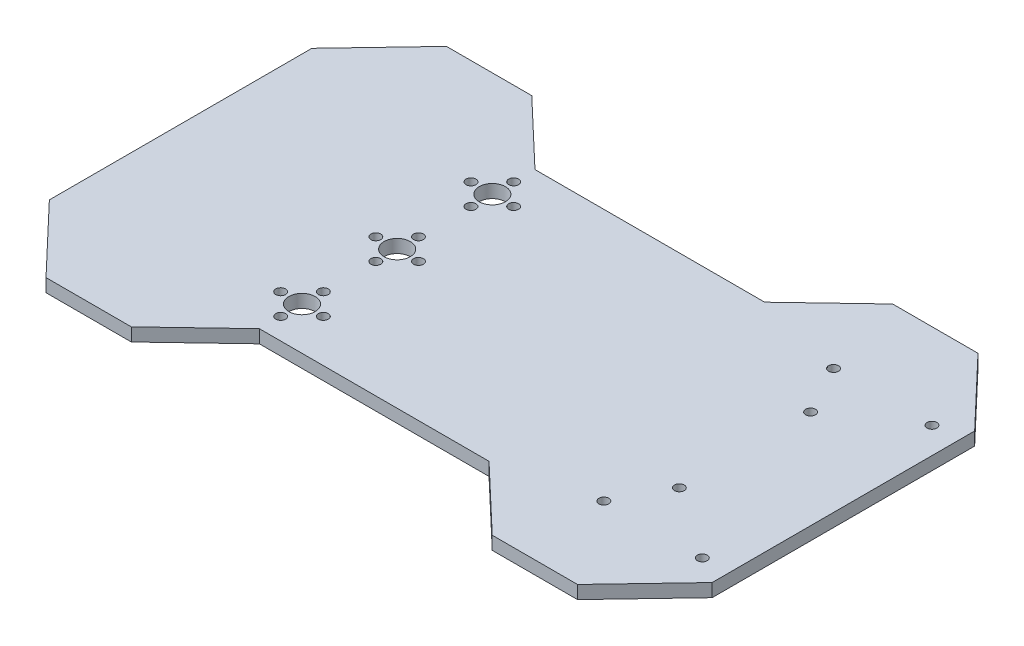
SolidWorks part; units mm, degrees
ref_plane "Front Plane" through (0, 0, 0) normal (0, 0, 1) x (1, 0, 0)
ref_plane "Top Plane" through (0, 0, 0) normal (0, 1, 0) x (1, 0, 0)
ref_plane "Right Plane" through (0, 0, 0) normal (1, 0, 0) x (0, 0, -1)
sketch "Sketch1" plane through (0, 0, 0) normal (0, 1, 0) x (1, 0, 0)
  line L0 (-101, 0) -> (101, 0) construction
  line L13 (-55, 61.025) -> (-35, 42)
  line L20 (-81, 61.025) -> (-55, 61.025)
  line L21 (-101, 40) -> (-81, 61.025)
  line L22 (-101, 40) -> (-101, -40)
  line L23 (-35, 42) -> (35, 42)
  line L24 (0, 42) -> (0, -42) construction
  line L25 (81, 61.025) -> (55, 61.025)
  line L26 (55, 61.025) -> (35, 42)
  line L27 (101, 40) -> (101, -40)
  line L28 (101, 40) -> (81, 61.025)
  line L37 (55, -61.025) -> (35, -42)
  line L38 (81, -61.025) -> (55, -61.025)
  line L39 (101, -40) -> (81, -61.025)
  line L40 (-81, -61.025) -> (-55, -61.025)
  line L41 (-55, -61.025) -> (-35, -42)
  line L42 (-101, -40) -> (-81, -61.025)
  line L46 (-35, -42) -> (35, -42)
  point P0 (0, 0)
  point P16 (0, 0)
  dimension "D1" = 20
  dimension "D2" = 84
  dimension "D3" = 40
  dimension "D4" = 35
  dimension "D5" = 26
  dimension "D6" = 202
extrude "Boss-Extrude1" add sketch "Sketch1" along normal blind 4
sketch "Sketch2" plane through (0, 4, 0) normal (0, 1, 0) x (1, 0, 0)
  line L0 (-101, 0) -> (101, 0) construction
  line L1 (-101, 40) -> (-101, -40) construction
  line L2 (101, -40) -> (101, 40) construction
sketch "Sketch3" plane through (0, 4, 0) normal (0, 1, 0) x (1, 0, 0)
  line L0 (0, 42) -> (0, -42) construction
  line L1 (35, 42) -> (-35, 42) construction
  line L2 (-35, -42) -> (35, -42) construction
  line L3 (-101, 0) -> (101, 0) construction
  circle A0 centre (-35, -29) radius 4
  circle A1 centre (-28.5, -29) radius 1.5
  circle A2 centre (-41.5, -29) radius 1.5
  circle A3 centre (-35, -22.5) radius 1.5
  circle A4 centre (-35, -35.5) radius 1.5
  circle A5 centre (-35, 35.5) radius 1.5
  circle A6 centre (-35, 22.5) radius 1.5
  circle A7 centre (-41.5, 29) radius 1.5
  circle A8 centre (-28.5, 29) radius 1.5
  circle A9 centre (-35, 29) radius 4
  circle A10 centre (-35, 0) radius 4
  circle A11 centre (-35, 6.5) radius 1.5
  circle A12 centre (-28.5, 0) radius 1.5
  circle A13 centre (-41.5, 0) radius 1.5
  circle A14 centre (-35, -6.5) radius 1.5
  point P40 (0, 0)
  point P41 (0, 0)
  dimension "D1" = 3
  dimension "D2" = 3
  dimension "D3" = 3
  dimension "D4" = 3
  dimension "D5" = 8
  dimension "D6" = 6.5
  dimension "D7" = 6.5
  dimension "D8" = 6.5
  dimension "D9" = 6.5
  dimension "D10" = 35
  dimension "D11" = 3
  dimension "D12" = 3
  dimension "D13" = 3
  dimension "D14" = 3
  dimension "D15" = 6.5
  dimension "D16" = 6.5
  dimension "D17" = 8
  dimension "D18" = 6.5
  dimension "D19" = 6.5
extrude "Cut-Extrude1" cut sketch "Sketch3" against normal through all
sketch "Sketch5" plane through (0, 4, 0) normal (0, 1, 0) x (1, 0, 0)
  line L0 (101, -40) -> (101, 40) construction
  line L1 (101, 0) -> (0, 0) construction
  circle A0 centre (93, 35) radius 1.5
  circle A1 centre (63, 35) radius 1.5
  circle A2 centre (63, -35) radius 1.5
  circle A3 centre (93, -35) radius 1.5
  dimension "D1" = 3
  dimension "D2" = 3
  dimension "D3" = 8
  dimension "D4" = 70
  dimension "D5" = 30
extrude "Cut-Extrude2" cut sketch "Sketch5" against normal through all
sketch "Sketch6" plane through (0, 0, 0) normal (0, -1, 0) x (1, 0, 0)
  line L0 (101, 40) -> (101, -40) construction
  circle A0 centre (71, 20) radius 1.5
  circle A1 centre (71, -20) radius 1.5
  point P4 (0, 0)
  dimension "D1" = 3
  dimension "D2" = 3
  dimension "D3" = 40
  dimension "D4" = 30
  dimension "D5" = 20
extrude "Cut-Extrude3" cut sketch "Sketch6" against normal through all
